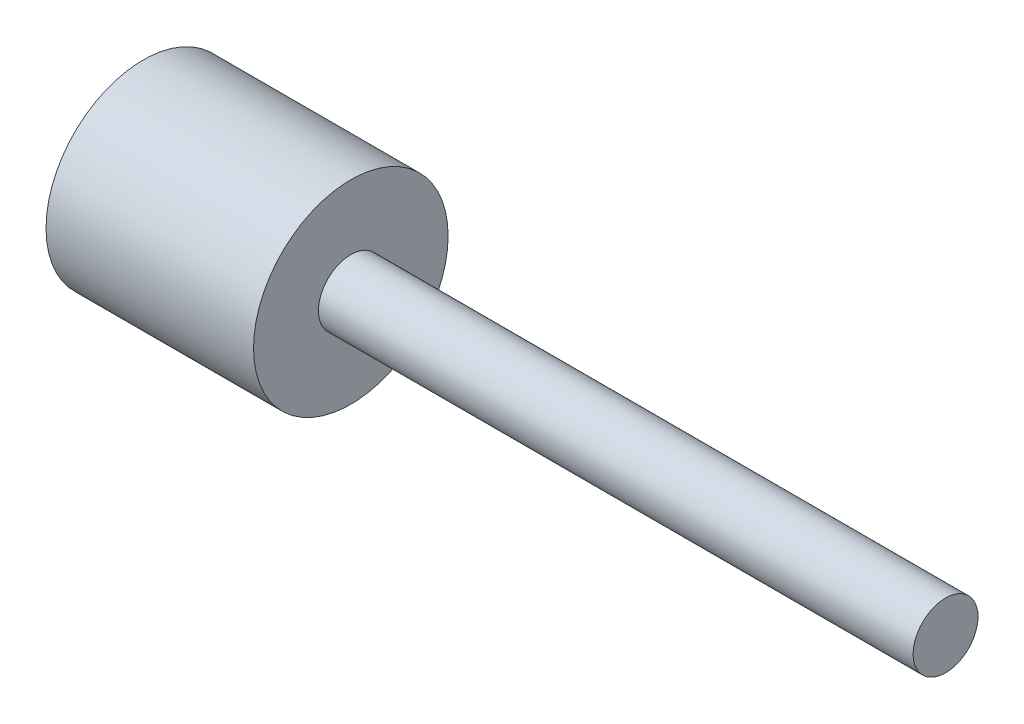
SolidWorks part; units mm, degrees
ref_plane "Front Plane" through (0, 0, 0) normal (0, 0, 1) x (1, 0, 0)
ref_plane "Top Plane" through (0, 0, 0) normal (0, 1, 0) x (1, 0, 0)
ref_plane "Right Plane" through (0, 0, 0) normal (1, 0, 0) x (0, 0, -1)
sketch "Sketch1" plane through (0, 0, 0) normal (1, 0, 0) x (0, 0, -1)
  circle A0 centre (0, 0) radius 7.5
  dimension "D1" = 15
extrude "Boss-Extrude1" add sketch "Sketch1" along normal blind 16
sketch "Sketch2" plane through (16, 0, 0) normal (1, 0, 0) x (0, 0, -1)
  circle A0 centre (0, 0) radius 2.5
  dimension "D1" = 5
extrude "Boss-Extrude2" add sketch "Sketch2" along normal up to vertex (45.85 mm away)
sketch "Sketch3" plane through (0, 0, 0) normal (-1, 0, 0) x (0, 0, 1)
  line L0 (0, 3) -> (0, -2) construction
  line L1 (-2.2361, -2) -> (2.2361, -2) construction
  line L2 (-2.4495, -2.5) -> (2.4495, -2.5)
  arc A0 (2.2361, -2) -> (-2.2361, -2) centre (0, 0) ccw construction
  arc A1 (2.4495, -2.5) -> (-2.4495, -2.5) centre (0, 0) ccw
  dimension "D1" = 6
  dimension "D2" = 5
  dimension "D3" = 0.5
extrude "Cut-Extrude1" cut sketch "Sketch3" against normal blind 12
sketch "Sketch4" plane through (0, -2.5, 0) normal (0, 1, 0) x (1, 0, 0)
  line L0 (0, 0) -> (16, 0) construction
  line L1 (16, -7.5) -> (16, 7.5) construction
  circle A0 centre (5, 0) radius 1.5
  dimension "D1" = 5
  dimension "D2" = 3
extrude "Cut-Extrude2" cut sketch "Sketch4" against normal up to next
